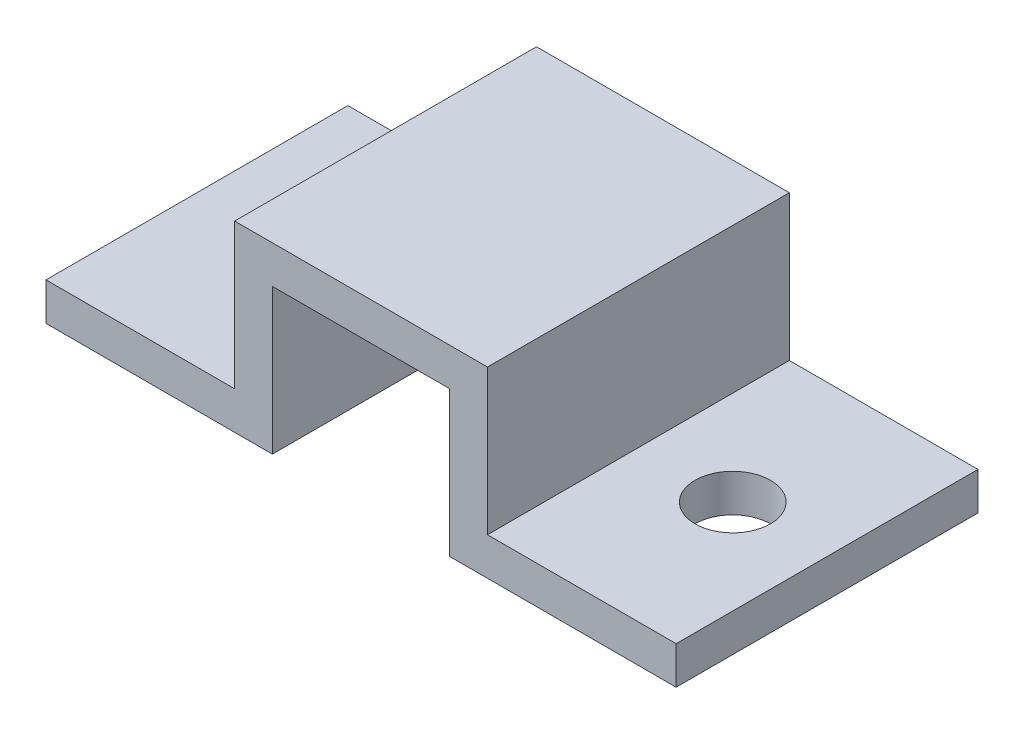
SolidWorks part; units mm, degrees
ref_plane "Front Plane" through (0, 0, 0) normal (0, 0, 1) x (1, 0, 0)
ref_plane "Top Plane" through (0, 0, 0) normal (0, 1, 0) x (1, 0, 0)
ref_plane "Right Plane" through (0, 0, 0) normal (1, 0, 0) x (0, 0, -1)
sketch "Sketch2" plane through (0, 0, 0) normal (0, 1, 0) x (1, 0, 0)
  line L1 (-5.5986, 4.8018) -> (36.8194, 4.8018)
  line L2 (-5.5986, 4.8018) -> (-5.5986, -15.5182)
  line L3 (-5.5986, -15.5182) -> (36.8194, -15.5182)
  line L4 (36.8194, 4.8018) -> (36.8194, -15.5182)
  dimension "D1" = 42.418
  dimension "D2" = 20.32
extrude "Boss-Extrude1" add sketch "Sketch2" along normal blind 12.319
sketch "Sketch5" plane through (0, 12.319, 0) normal (0, 1, 0) x (1, 0, 0)
  line L0 (-5.5986, -15.5182) -> (36.8194, -15.5182) construction
  line L1 (-5.5986, 4.8018) -> (7.1014, 4.8018)
  line L2 (-5.5986, 4.8018) -> (-5.5986, -15.5182)
  line L3 (-5.5986, -15.5182) -> (7.1014, -15.5182)
  line L4 (7.1014, 4.8018) -> (7.1014, -15.5182)
  dimension "D1" = 12.7
extrude "Cut-Extrude1" cut sketch "Sketch5" against normal blind 9.779
sketch "Sketch6" plane through (0, 12.319, 0) normal (0, 1, 0) x (1, 0, 0)
  line L0 (36.8194, 4.8018) -> (7.1014, 4.8018) construction
  line L1 (36.8194, -15.5182) -> (24.1194, -15.5182)
  line L2 (36.8194, -15.5182) -> (36.8194, 4.8018)
  line L3 (36.8194, 4.8018) -> (24.1194, 4.8018)
  line L4 (24.1194, -15.5182) -> (24.1194, 4.8018)
  dimension "D1" = 12.7
extrude "Cut-Extrude2" cut sketch "Sketch6" against normal blind 9.779
sketch "Sketch7" plane through (0, 0, 0) normal (0, -1, 0) x (-1, 0, 0)
  line L0 (5.5986, -15.5182) -> (-36.8194, -15.5182) construction
  line L1 (-9.6414, -15.5182) -> (-21.5794, -15.5182)
  line L2 (-9.6414, -15.5182) -> (-9.6414, 4.8018)
  line L3 (-9.6414, 4.8018) -> (-21.5794, 4.8018)
  line L4 (-21.5794, -15.5182) -> (-21.5794, 4.8018)
  line L5 (-36.8194, 4.8018) -> (5.5986, 4.8018) construction
  line L6 (5.5986, 4.8018) -> (5.5986, -15.5182) construction
  dimension "D1" = 11.938
  dimension "D2" = 15.24
extrude "Cut-Extrude3" cut sketch "Sketch7" against normal blind 9.779
sketch "Sketch8" plane through (0, 2.54, 0) normal (0, 1, 0) x (1, 0, 0)
  line L0 (-5.5986, -15.5182) -> (7.1014, -15.5182) construction
  line L1 (-5.5986, 4.8018) -> (-5.5986, -15.5182) construction
  circle A0 centre (0.7514, -5.3582) radius 2.54
  dimension "D1" = 10.16
  dimension "D2" = 6.35
extrude "Cut-Extrude4" cut sketch "Sketch8" against normal blind 2.54
sketch "Sketch9" plane through (0, 2.54, 0) normal (0, 1, 0) x (1, 0, 0)
  line L0 (36.8194, -15.5182) -> (36.8194, 4.8018) construction
  line L1 (36.8194, 4.8018) -> (24.1194, 4.8018) construction
  circle A0 centre (30.4694, -5.3582) radius 2.54
  dimension "D1" = 6.35
  dimension "D2" = 10.16
extrude "Cut-Extrude5" cut sketch "Sketch9" against normal blind 2.54
